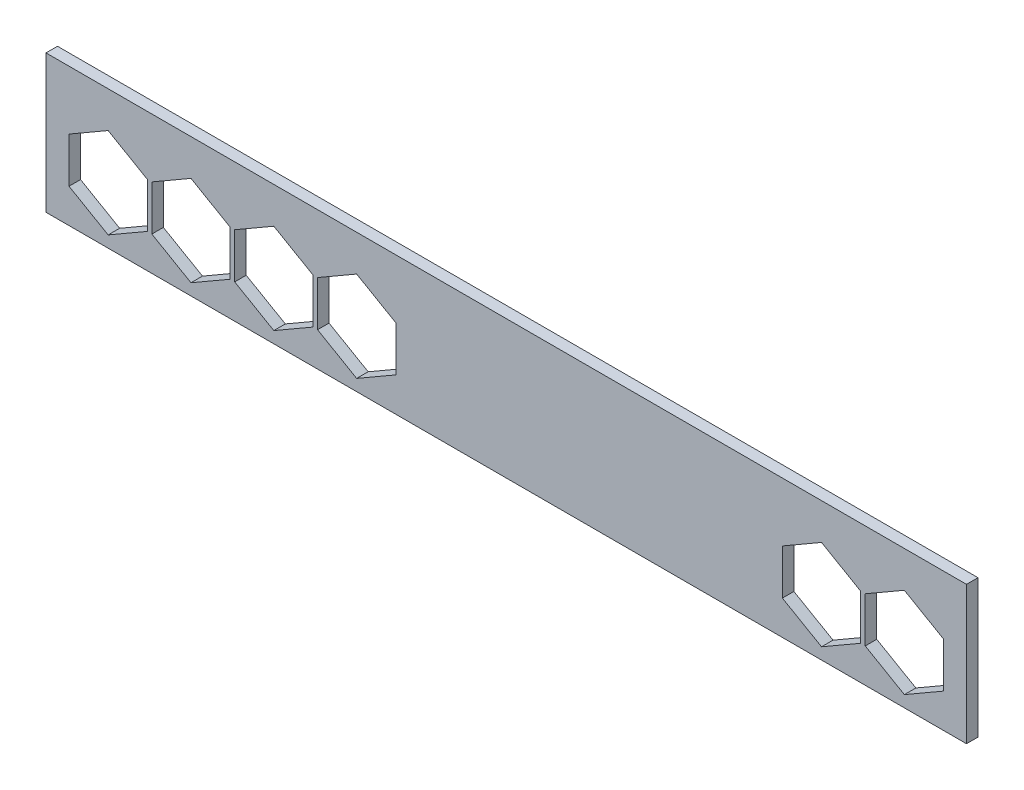
SolidWorks part; units mm, degrees
ref_plane "Front Plane" through (0, 0, 0) normal (0, 0, 1) x (1, 0, 0)
ref_plane "Top Plane" through (0, 0, 0) normal (0, 1, 0) x (1, 0, 0)
ref_plane "Right Plane" through (0, 0, 0) normal (1, 0, 0) x (0, 0, -1)
sketch "Sketch1" plane through (0, 0, 0) normal (0, 0, 1) x (1, 0, 0)
  line L1 (127, -19.05) -> (-127, -19.05)
  line L2 (127, -19.05) -> (127, 19.05)
  line L3 (127, 19.05) -> (-127, 19.05)
  line L4 (-127, -19.05) -> (-127, 19.05)
  line L5 (127, -19.05) -> (-127, 19.05) construction
  line L6 (127, 19.05) -> (-127, -19.05) construction
  point P0 (0, 0)
  dimension "D1" = 254
  dimension "D2" = 38.1
extrude "Boss-Extrude1" add sketch "Sketch1" along normal blind 3.175
sketch "Sketch4" plane through (0, 0, 3.175) normal (0, 0, 1) x (1, 0, 0)
  line L1 (-118.11, 9.0548) -> (-33.02, 9.0548) construction
  line L2 (-120.65, 6.5148) -> (-120.65, -13.335) construction
  line L3 (-118.11, -15.875) -> (-33.02, -15.875) construction
  line L4 (-30.48, 6.5148) -> (-30.48, -13.335) construction
  line L5 (-118.11, 12.2298) -> (-33.02, 12.2298) construction
  line L6 (-27.305, 6.5148) -> (-27.305, -13.335) construction
  line L7 (-118.11, -19.05) -> (-33.02, -19.05) construction
  line L8 (-123.825, 6.5148) -> (-123.825, -13.335) construction
  line L10 (-127, -19.05) -> (127, -19.05) construction
  line L11 (-127, 19.05) -> (-127, -19.05) construction
  line L13 (-99.0601, -9.6425) -> (-99.0601, 2.8224)
  line L14 (-99.0601, 2.8224) -> (-109.8551, 9.0548)
  line L15 (-109.8551, 9.0548) -> (-120.65, 2.8224)
  line L16 (-120.65, 2.8224) -> (-120.65, -9.6425)
  line L17 (-120.65, -9.6425) -> (-109.8551, -15.875)
  line L18 (-109.8551, -15.875) -> (-99.0601, -9.6425)
  line L19 (-76.2001, -9.6425) -> (-76.2001, 2.8224)
  line L20 (-76.2001, 2.8224) -> (-86.9951, 9.0548)
  line L21 (-86.9951, 9.0548) -> (-97.79, 2.8224)
  line L22 (-97.79, 2.8224) -> (-97.79, -9.6425)
  line L23 (-97.79, -9.6425) -> (-86.9951, -15.875)
  line L24 (-86.9951, -15.875) -> (-76.2001, -9.6425)
  line L25 (-53.3401, -9.6425) -> (-53.3401, 2.8224)
  line L26 (-53.3401, 2.8224) -> (-64.1351, 9.0548)
  line L27 (-64.1351, 9.0548) -> (-74.93, 2.8224)
  line L28 (-74.93, 2.8224) -> (-74.93, -9.6425)
  line L29 (-74.93, -9.6425) -> (-64.1351, -15.875)
  line L30 (-64.1351, -15.875) -> (-53.3401, -9.6425)
  line L31 (-30.4801, -9.6425) -> (-30.4801, 2.8224)
  line L32 (-30.4801, 2.8224) -> (-41.2751, 9.0548)
  line L33 (-41.2751, 9.0548) -> (-52.07, 2.8224)
  line L34 (-52.07, 2.8224) -> (-52.07, -9.6425)
  line L35 (-52.07, -9.6425) -> (-41.2751, -15.875)
  line L36 (-41.2751, -15.875) -> (-30.4801, -9.6425)
  line L37 (127, -19.05) -> (127, 19.05) construction
  line L38 (120.65, -9.6425) -> (120.65, 2.8224)
  line L39 (120.65, 2.8224) -> (109.8551, 9.0548)
  line L40 (109.8551, 9.0548) -> (99.0601, 2.8224)
  line L41 (99.0601, 2.8224) -> (99.0601, -9.6425)
  line L42 (99.0601, -9.6425) -> (109.8551, -15.875)
  line L43 (109.8551, -15.875) -> (120.65, -9.6425)
  line L44 (97.79, -9.6425) -> (97.79, 2.8224)
  line L45 (97.79, 2.8224) -> (86.9951, 9.0548)
  line L46 (86.9951, 9.0548) -> (76.2001, 2.8224)
  line L47 (76.2001, 2.8224) -> (76.2001, -9.6425)
  line L48 (76.2001, -9.6425) -> (86.9951, -15.875)
  line L49 (86.9951, -15.875) -> (97.79, -9.6425)
  arc A0 (-120.65, -13.335) -> (-118.11, -15.875) centre (-118.11, -13.335) ccw construction
  arc A1 (-30.48, -13.335) -> (-33.02, -15.875) centre (-33.02, -13.335) cw construction
  arc A2 (-30.48, 6.5148) -> (-33.02, 9.0548) centre (-33.02, 6.5148) ccw construction
  arc A3 (-120.65, 6.5148) -> (-118.11, 9.0548) centre (-118.11, 6.5148) cw construction
  arc A4 (-27.305, 6.5148) -> (-33.02, 12.2298) centre (-33.02, 6.5148) ccw construction
  arc A5 (-27.305, -13.335) -> (-33.02, -19.05) centre (-33.02, -13.335) cw construction
  arc A6 (-123.825, -13.335) -> (-118.11, -19.05) centre (-118.11, -13.335) ccw construction
  arc A7 (-123.825, 6.5148) -> (-118.11, 12.2298) centre (-118.11, 6.5148) cw construction
  circle A8 centre (-109.8551, -3.4101) radius 10.7949 construction
  circle A9 centre (-109.8551, -3.4101) radius 12.4649 construction
  circle A10 centre (109.8551, -3.4101) radius 10.7949 construction
  dimension "D1" = 90.17
  dimension "D4" = 2.54
  dimension "D5" = 3.175
  dimension "D6" = 3.175
  dimension "D3" = 2.54
  dimension "D2" = 24.9298
  dimension "D8" = 22.86
  dimension "D9" = 6.35
  dimension "D7" = 4
  dimension "D10" = 2
extrude "Cut-Extrude1" cut sketch "Sketch4" against normal blind 10.414
